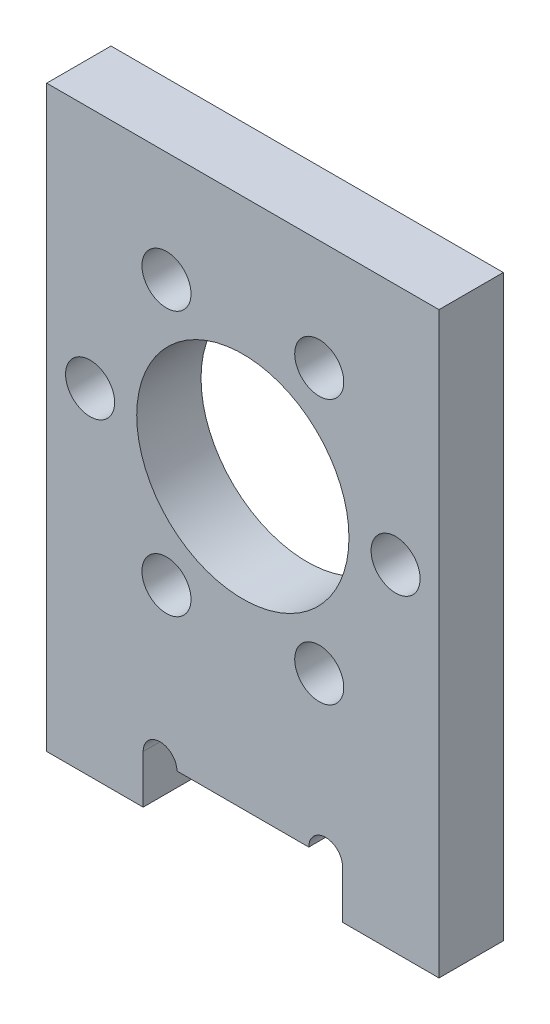
SolidWorks part; units mm, degrees
material "Thornel Mat VMA"
ref_plane "前视基准面" through (0, 0, 0) normal (0, 0, 1) x (1, 0, 0)
ref_plane "上视基准面" through (0, 0, 0) normal (0, 1, 0) x (1, 0, 0)
ref_plane "右视基准面" through (0, 0, 0) normal (1, 0, 0) x (0, 0, -1)
other "Configuration Table"
sketch "草图2" plane through (0, 0, 0) normal (0, 0, 1) x (1, 0, 0)
  line L1 (-12.2, -16.5) -> (12.2, -16.5)
  line L2 (-12.2, -16.5) -> (-12.2, 16.5)
  line L3 (-12.2, 16.5) -> (12.2, 16.5)
  line L4 (12.2, -16.5) -> (12.2, 16.5)
  line L5 (-12.2, -16.5) -> (12.2, 16.5) construction
  line L6 (-12.2, 16.5) -> (12.2, -16.5) construction
  point P0 (0, 0)
  dimension "D1" = 24.4
  dimension "D2" = 33
extrude "凸台-拉伸1" add sketch "草图2" along normal blind 4
sketch "草图3" plane through (0, 0, 4) normal (0, 0, 1) x (1, 0, 0)
  circle A0 centre (0, 1.4101) radius 6.5 construction
  circle A1 centre (0, 1.4101) radius 6.5 construction
  circle A2 centre (0, 1.4101) radius 6.6
  dimension "D1" = 0.1
extrude "切除-拉伸1" cut sketch "草图3" against normal blind 4
sketch "草图4" plane through (0, 0, 4) normal (0, 0, 1) x (1, 0, 0)
  line L1 (12.2, -16.5) -> (6.2, -16.5)
  line L2 (12.2, -16.5) -> (12.2, -19.5)
  line L3 (12.2, -19.5) -> (6.2, -19.5)
  line L4 (6.2, -16.5) -> (6.2, -19.5)
  dimension "D1" = 3
  dimension "D2" = 6
extrude "凸台-拉伸2" add sketch "草图4" against normal up to surface (4 mm away) up to face at (6.6, 1.4101, 0)
mirror "镜向1" about plane through (0, 0, 0) normal (1, 0, 0) of "凸台-拉伸2"
sketch "草图5" plane through (0, 0, 0) normal (0, 0, -1) x (-1, 0, 0)
  line L0 (6.2, -16.5) -> (-6.2, -16.5) construction
  circle A0 centre (-5.15, -16.5) radius 1.05
  circle A1 centre (5.15, -16.5) radius 1.05
  dimension "D1" = 2.1
extrude "切除-拉伸2" cut sketch "草图5" against normal up to surface (4 mm away) up to face at (6.6, 1.4101, 4)
sketch "草图6" plane through (0, 0, 4) normal (0, 0, 1) x (1, 0, 0)
  circle A0 centre (-4.75, -6.8172) radius 1.25 construction
  circle A1 centre (9.5, 1.4101) radius 1.25 construction
  circle A2 centre (-4.75, 9.6373) radius 1.25 construction
  circle A3 centre (-4.75, -6.8172) radius 1.25 construction
  circle A4 centre (9.5, 1.4101) radius 1.25 construction
  circle A5 centre (-4.75, 9.6373) radius 1.25 construction
  circle A6 centre (-4.75, -6.8172) radius 1.525
  dimension "D1" = 3.05
extrude "切除-拉伸3" cut sketch "草图6" against normal up to surface (4 mm away) up to face at (0, -10.89, 0)
pattern_circular "阵列(圆周)1" count 6 over 360 about axis through (0, 1.4101, 0) along (0, 0, 1) of "切除-拉伸3"
